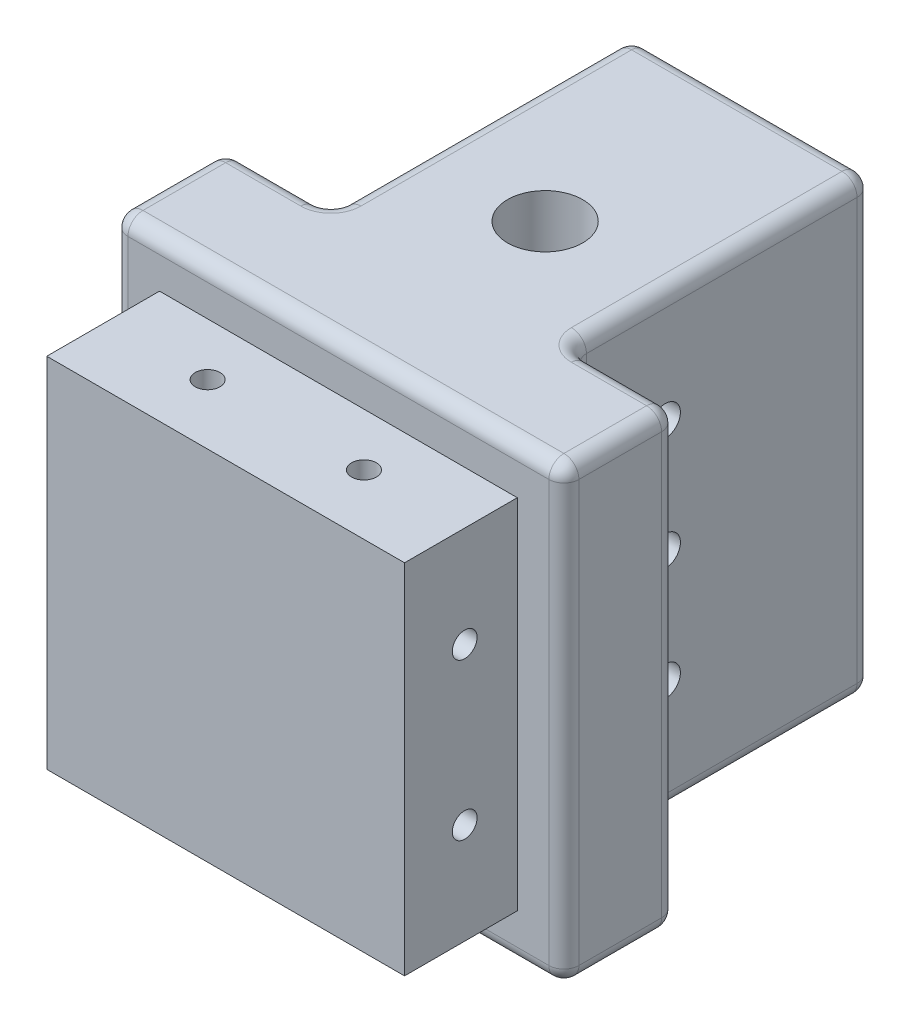
SolidWorks part; units mm, degrees
ref_plane "Front Plane" through (0, 0, 0) normal (0, 0, 1) x (1, 0, 0)
ref_plane "Top Plane" through (0, 0, 0) normal (0, 1, 0) x (1, 0, 0)
ref_plane "Right Plane" through (0, 0, 0) normal (1, 0, 0) x (0, 0, -1)
sketch "Sketch2" plane through (0, 0, 0) normal (0, 0, 1) x (1, 0, 0)
  line L1 (-30, -30) -> (30, -30)
  line L2 (-30, -30) -> (-30, 30)
  line L3 (-30, 30) -> (30, 30)
  line L4 (30, -30) -> (30, 30)
  line L5 (-30, -30) -> (30, 30) construction
  line L6 (-30, 30) -> (30, -30) construction
  point P0 (0, 0)
  dimension "D1" = 60
  dimension "D2" = 60
extrude "Boss-Extrude1" add sketch "Sketch2" along normal blind 70
sketch "Sketch3" plane through (0, 0, 70) normal (0, 0, 1) x (1, 0, 0)
  line L1 (-23.8, -23.8) -> (23.8, -23.8)
  line L2 (-23.8, -23.8) -> (-23.8, 23.8)
  line L3 (-23.8, 23.8) -> (23.8, 23.8)
  line L4 (23.8, -23.8) -> (23.8, 23.8)
  line L5 (-23.8, -23.8) -> (23.8, 23.8) construction
  line L6 (-23.8, 23.8) -> (23.8, -23.8) construction
  point P0 (0, 0)
  dimension "D1" = 47.6
  dimension "D2" = 47.6
extrude "Cut-Extrude1" cut sketch "Sketch3" against normal blind 15 flip side to cut
sketch "Sketch13" plane through (0, 0, 70) normal (0, 0, 1) x (1, 0, 0)
  point P0 (0, 0)
sketch "Sketch14" plane through (0, 0, 0) normal (1, 0, 0) x (0, 0, -1)
  line L0 (-70, 0) -> (0, 0) construction
hole_wizard "M4 Tapped Hole1" positions "Sketch15" profile "Sketch16" tap size "M4" standard "ISO"
sketch "Sketch15" plane through (23.8, 0, 0) normal (1, 0, 0) x (0, 0, -1)
  point P0 (-62, -10.4)
  point P2 (-62, 10.4)
  dimension "D1" = 7
  dimension "D2" = 13.4
  dimension "D3" = 13.4
  dimension "D4" = 7
sketch "Sketch16" plane through (23.8, -10.4, 62) normal (0, 1, 0) x (0, 0, -1)
  line L0 (0, 0) -> (0, 12.4914)
  line L1 (0, 12.4914) -> (1.65, 11.5)
  line L2 (1.65, 11.5) -> (1.65, 0)
  line L5 (1.65, 0) -> (0, 0)
  line L10 (0, 12.4914) -> (-1.65, 11.5) construction
  line L11 (0, -6.35) -> (0, 107.95) construction
  dimension "Tap Drill Dia." = 3.3
  dimension "Tap Drill Depth" = 11.5
  dimension "Drill Angle" = 118
cosmetic thread "Hole Thread1" parameters "D1"=8, "D2"=4
cosmetic thread "Hole Thread2" parameters "D1"=8, "D2"=4
sketch "Sketch17" plane through (0, 0, 70) normal (0, 0, 1) x (1, 0, 0)
  point P0 (0, 0)
sketch "Sketch18" plane through (0, 0, 0) normal (1, 0, 0) x (0, 0, -1)
  line L0 (-70, 0) -> (6.8187, 0) construction
pattern_circular "CirPattern1" count 4 every 90 about axis through (0, 0, 70) along (0, 0, -1) of "M4 Tapped Hole1"
sketch "Sketch19" plane through (0, 30, 0) normal (0, 1, 0) x (1, 0, 0)
  circle A0 centre (0, -27.5) radius 5
  dimension "D1" = 10
  dimension "D2" = 27.5
extrude "Cut-Extrude2" cut sketch "Sketch19" against normal through all
sketch "Sketch21" plane through (0, 0, 0) normal (0, 0, -1) x (-1, 0, 0)
  line L0 (30, -30) -> (-30, -30) construction
  line L1 (-30, 30) -> (-16, 30)
  line L2 (-30, 30) -> (-30, -30)
  line L3 (-30, -30) -> (-16, -30)
  line L4 (-16, 30) -> (-16, -30)
  dimension "D1" = 14
extrude "Cut-Extrude3" cut sketch "Sketch21" against normal blind 40
mirror "Mirror1" about plane through (0, 0, 0) normal (1, 0, 0) of "Cut-Extrude3"
hole_wizard "Ø4.0mm Dowel Hole1" positions "Sketch22" profile "Sketch23" hole size "Ø4.0" standard "ISO" end condition through all
sketch "Sketch22" plane through (-16, 0, 0) normal (-1, 0, 0) x (0, 0, 1)
  line L0 (0, -30) -> (0, 30) construction
  point P0 (27.5, 15)
  point P2 (27.5, 0)
  point P4 (27.5, -15)
  dimension "D1" = 27.5
  dimension "D2" = 27.5
  dimension "D3" = 27.5
  dimension "D4" = 15
  dimension "D5" = 30
  dimension "D6" = 15
sketch "Sketch23" plane through (-16, 15, 27.5) normal (0, 1, 0) x (0, 0, 1)
  line L0 (0, 0) -> (0, 46)
  line L1 (0, 46) -> (2, 46)
  line L2 (2, 46) -> (2, 0)
  line L5 (2, 0) -> (0, 0)
  line L11 (0, -6.35) -> (0, 107.95) construction
  dimension "Thru Hole Dia." = 4
  dimension "Thru Hole Depth" = 46
fillet "Fillet1" radius 2 24 edges at (16, 0, 40) (30, 0, 40) (-16, 0, 40) (-30, 0, 40) (16, 0, 0) (-16, 0, 0) (-23, -30, 40) (-30, -30, 47.5) (0, -30, 55) (30, -30, 47.5) (23, -30, 40) (16, -30, 20) (0, -30, 0) (-16, -30, 20) (0, 30, 0) (16, 30, 20) (23, 30, 40) (30, 30, 47.5) (0, 30, 55) (-30, 30, 47.5) (-23, 30, 40) (-16, 30, 20) (-30, 0, 55) (30, 0, 55)
